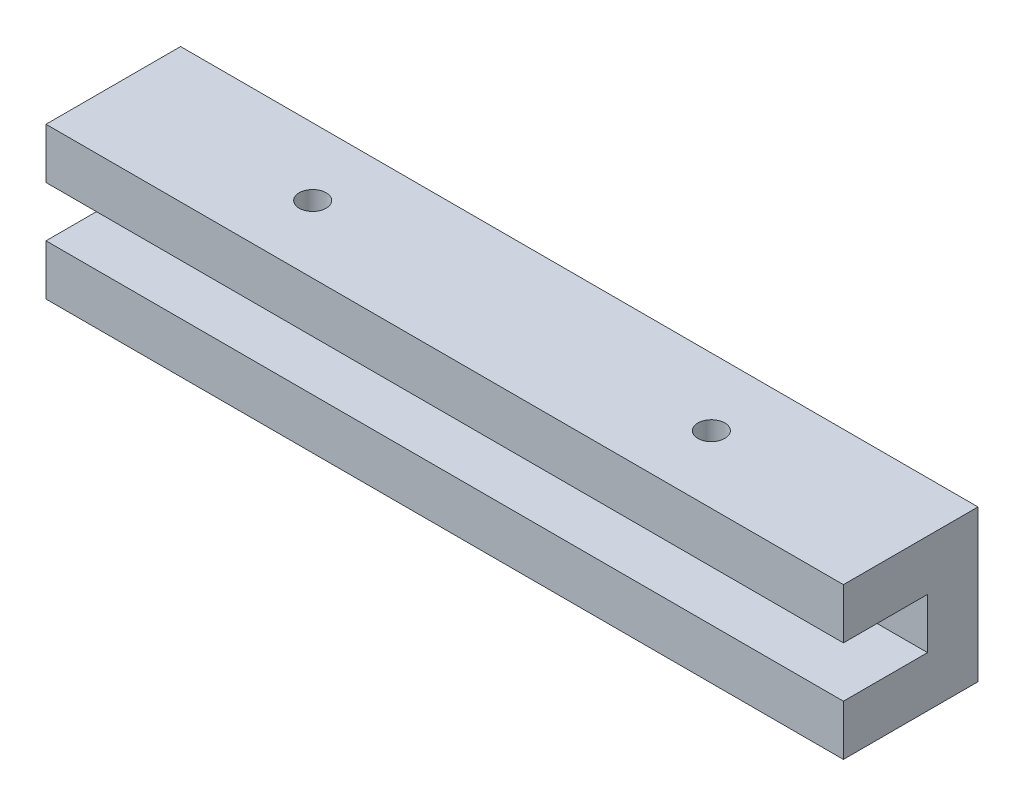
SolidWorks part; units mm, degrees
ref_plane "Front Plane" through (0, 0, 0) normal (0, 0, 1) x (1, 0, 0)
ref_plane "Top Plane" through (0, 0, 0) normal (0, 1, 0) x (1, 0, 0)
ref_plane "Right Plane" through (0, 0, 0) normal (1, 0, 0) x (0, 0, -1)
sketch "Sketch1" plane through (0, 0, 0) normal (0, 1, 0) x (1, 0, 0)
  line L1 (-14.6309, 13.4784) -> (32.7691, 13.4784)
  line L2 (-14.6309, 13.4784) -> (-14.6309, 5.4784)
  line L3 (-14.6309, 5.4784) -> (32.7691, 5.4784)
  line L4 (32.7691, 13.4784) -> (32.7691, 5.4784)
  dimension "D1" = 47.4
  dimension "D2" = 8
extrude "Boss-Extrude1" add sketch "Sketch1" along normal blind 9
sketch "Sketch2" plane through (32.7691, 0, 0) normal (1, 0, 0) x (0, 0, -1)
  line L3 (5.4784, 3) -> (10.4784, 3)
  line L5 (5.4784, 3) -> (5.4784, 6)
  line L6 (5.4784, 6) -> (10.4784, 6)
  line L7 (10.4784, 3) -> (10.4784, 6)
  dimension "D1" = 5
extrude "Cut-Extrude1" cut sketch "Sketch2" against normal blind 58 and the other way blind 17
sketch "Sketch3" plane through (0, 9, 0) normal (0, 1, 0) x (1, 0, 0)
  line L0 (-14.6309, 13.4784) -> (9.0691, 13.4784)
  line L1 (32.7691, 13.4784) -> (-14.6309, 13.4784) construction
  line L2 (9.0691, 13.4784) -> (32.7691, 13.4784)
  line L3 (-2.7809, 13.4784) -> (-2.7809, 5.4784)
  line L4 (-14.6309, 5.4784) -> (32.7691, 5.4784) construction
  line L5 (20.9191, 13.4784) -> (20.9191, 5.4784)
  point P11 (-2.7809, 9.4784)
  point P14 (20.9191, 9.4784)
hole_wizard "M2x0.4 Tapped Hole1" positions "Sketch4" profile "Sketch5" tap size "M2x0.4" standard "ANSI Metric" end condition through all
sketch "Sketch4" plane through (0, 9, 0) normal (0, 1, 0) x (1, 0, 0)
  point P0 (-2.7809, 9.4784)
  point P3 (20.9191, 9.4784)
sketch "Sketch5" plane through (-2.7809, 9, -9.4784) normal (1, 0, 0) x (0, 0, 1)
  line L0 (0, 0) -> (0, 9)
  line L1 (0, 9) -> (0.8, 9)
  line L2 (0.8, 9) -> (0.8, 0)
  line L5 (0.8, 0) -> (0, 0)
  line L11 (0, -6.35) -> (0, 107.95) construction
  dimension "Thru Tap Drill Dia." = 1.6
  dimension "Thru Tap Drill Depth" = 9
cosmetic thread "Hole Thread1" parameters "D2"=2
cosmetic thread "Hole Thread2" parameters "D2"=2
sketch "Sketch6" plane through (0, 0, -10.4784) normal (0, 0, 1) x (1, 0, 0)
  line L0 (-14.6309, 6) -> (32.7691, 6)
  line L1 (-14.6309, 3) -> (32.7691, 3)
  point P4 (9.0691, 6)
  point P9 (9.0691, 3)
  point P10 (-14.6309, -1.3061)
